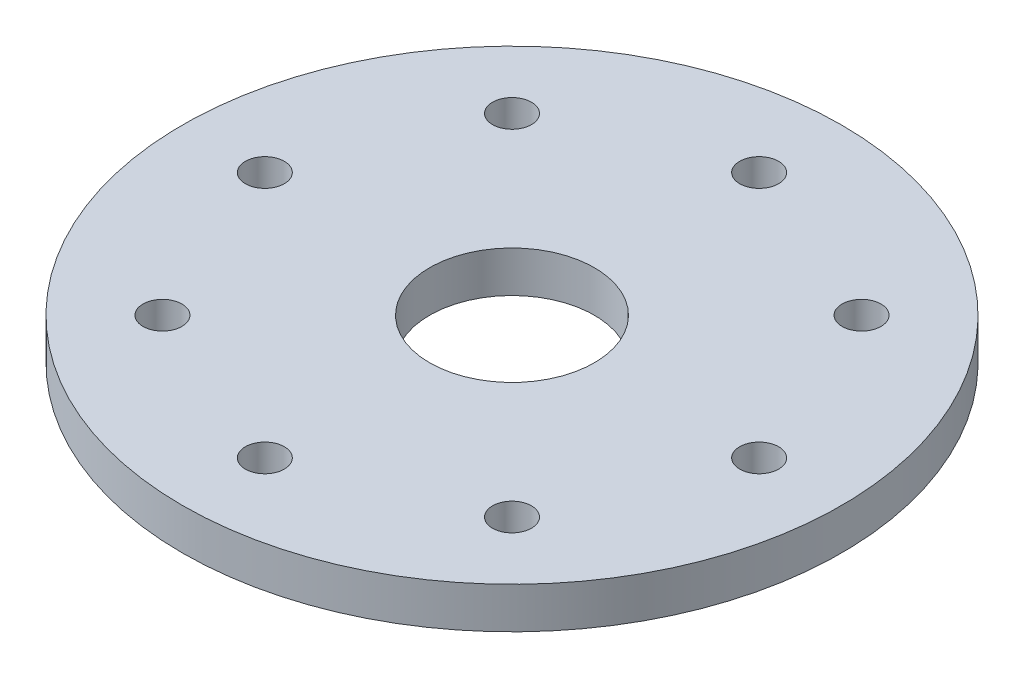
SolidWorks part; units mm, degrees
ref_plane "Front Plane" through (0, 0, 0) normal (0, 0, 1) x (1, 0, 0)
ref_plane "Top Plane" through (0, 0, 0) normal (0, 1, 0) x (1, 0, 0)
ref_plane "Right Plane" through (0, 0, 0) normal (1, 0, 0) x (0, 0, -1)
sketch "Sketch1" plane through (0, 0, 0) normal (0, 1, 0) x (1, 0, 0)
  circle A0 centre (0, 0) radius 6.35
  circle A1 centre (0, 19.05) radius 1.5
  circle A2 centre (13.4704, 13.4704) radius 1.5
  circle A3 centre (19.05, 0) radius 1.5
  circle A4 centre (13.4704, -13.4704) radius 1.5
  circle A5 centre (0, -19.05) radius 1.5
  circle A6 centre (-13.4704, -13.4704) radius 1.5
  circle A7 centre (-19.05, 0) radius 1.5
  circle A8 centre (-13.4704, 13.4704) radius 1.5
  circle A9 centre (0, 0) radius 25.4
  point P14 (0, 0)
  dimension "D1" = 12.7
  dimension "D2" = 3
  dimension "D5" = 50.8
  dimension "D3" = 19.05
  dimension "D4" = 8
extrude "Boss-Extrude1" add sketch "Sketch1" along normal blind 3.175
equation "\"D1@Sketch1\" = \"1/4 bolt@Arm.Assembly\" * 2"
equation "\"D2@Sketch1\" = \"3mm bolt@Arm.Assembly\""
equation "\"D3@Sketch1\"=\"med wall@arm.assembly\"*3"
equation "\"D4@Sketch1\"=\"base screw num@arm.assembly\""
equation "\"D5@Sketch1\"=(\"med wall@arm.assembly\"*8)"
equation "\"D1@Boss-Extrude1\"=\"thin wall@arm.assembly\""
